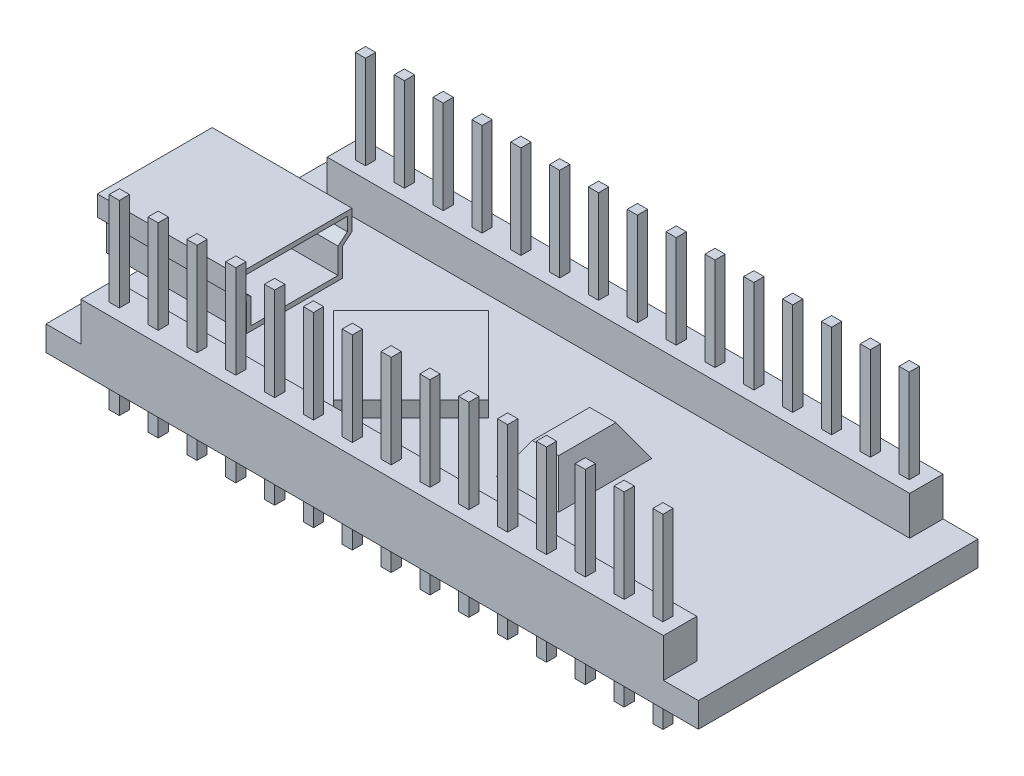
SolidWorks part; units mm, degrees
ref_plane "Front Plane" through (0, 0, 0) normal (0, 0, 1) x (1, 0, 0)
ref_plane "Top Plane" through (0, 0, 0) normal (0, 1, 0) x (1, 0, 0)
ref_plane "Right Plane" through (0, 0, 0) normal (1, 0, 0) x (0, 0, -1)
sketch "Sketch1" plane through (0, 0, 0) normal (0, 1, 0) x (1, 0, 0)
  line L1 (0, 0) -> (42, 0)
  line L2 (0, 0) -> (0, 18)
  line L3 (0, 18) -> (42, 18)
  line L4 (42, 0) -> (42, 18)
  dimension "D1" = 18
  dimension "D2" = 42
extrude "Boss-Extrude1" add sketch "Sketch1" along normal blind 1.6
sketch "Sketch2" plane through (0, 0, 0) normal (-1, 0, 0) x (0, 0, 1)
  line L0 (-9, 1.6) -> (-9, 5.2) construction
  line L1 (-18, 1.6) -> (0, 1.6) construction
  line L2 (-9, 1.6) -> (-12.1, 1.6)
  line L3 (-12.1, 1.6) -> (-12.1, 3.4)
  line L4 (-12.1, 3.4) -> (-12.7, 3.9)
  line L5 (-12.7, 3.9) -> (-12.7, 5.2)
  line L6 (-12.7, 5.2) -> (-9, 5.2)
  dimension "D1" = 3.6
  dimension "D2" = 3.7
  dimension "D3" = 3.1
  dimension "D4" = 1.8
  dimension "D5" = 1.3
extrude "Extrude-Thin1" add sketch "Sketch2" against normal blind 7 and the other way blind 2 thin
ref_plane "Plane1" through (0, 0, -9) normal (0, 0, 1) x (1, 0, 0)
mirror "Mirror1" about plane through (0, 0, -9) normal (0, 0, 1) of "Extrude-Thin1"
sketch "Sketch3" plane through (0, 1.6, 0) normal (0, -1, 0) x (1, 0, 0)
  line L0 (0, 0) -> (42, 0) construction
  line L1 (2.25, 0) -> (39.75, 0)
  line L2 (21, 0) -> (21, -2.1483)
  line L3 (2.25, -2.1483) -> (39.75, -2.1483)
  line L4 (39.75, 0) -> (39.75, -2.1483)
  line L5 (2.25, 0) -> (2.25, -2.1483)
  line M13 (0, 0) -> (42, 0)
  dimension "D1" = 18.75
  dimension "D2" = 2.1483
extrude "Boss-Extrude2" add sketch "Sketch3" against normal blind 2.5 contours L5 L2 L3 M13 | L1 L4 L3 L2
sketch "Sketch4" plane through (0, 4.1, 0) normal (0, -1, 0) x (1, 0, 0)
  line L0 (2.25, -1.0741) -> (3.6453, -1.0741) construction
  line L1 (2.25, 0) -> (2.25, -2.1483) construction
  line L3 (3.9727, -0.7468) -> (3.318, -0.7468)
  line L4 (3.9727, -0.7468) -> (3.9727, -1.4015)
  line L5 (3.9727, -1.4015) -> (3.318, -1.4015)
  line L6 (3.318, -0.7468) -> (3.318, -1.4015)
  line L7 (3.9727, -0.7468) -> (3.318, -1.4015) construction
  line L8 (3.9727, -1.4015) -> (3.318, -0.7468) construction
extrude "Boss-Extrude3" add sketch "Sketch4" along normal blind 6 and the other way blind 6
pattern_linear "LPattern1" count 15 spacing 2.5 along (1, 0, 0) of "Boss-Extrude3"
mirror "Mirror3" about plane through (0, 0, -9) normal (0, 0, 1) of "Boss-Extrude2"
mirror "Mirror4" about plane through (0, 0, -9) normal (0, 0, 1) of "LPattern1", "Boss-Extrude3"
sketch "Эскиз2" plane through (0, 1.6, 0) normal (0, 1, 0) x (1, 0, 0)
  line L0 (42, 9) -> (25, 9) construction
  line L1 (42, 0) -> (42, 18) construction
  line L3 (27, 12) -> (23, 12)
  line L4 (27, 12) -> (27, 6)
  line L5 (27, 6) -> (23, 6)
  line L6 (23, 12) -> (23, 6)
  line L7 (27, 12) -> (23, 6) construction
  line L8 (27, 6) -> (23, 12) construction
  dimension "D1" = 17
  dimension "D2" = 4
  dimension "D3" = 6
extrude "Бобышка-Вытянуть2" add sketch "Эскиз2" along normal blind 2 draft 30
sketch "Эскиз3" plane through (0, 1.6, 0) normal (0, 1, 0) x (1, 0, 0)
  line L0 (42, 9) -> (14.5, 9) construction
  line L1 (42, 0) -> (42, 18) construction
  line L2 (14.5, 9) -> (14.5, 4) construction
  line L3 (14.5, 4) -> (19.5, 9)
  line L4 (14.5, 4) -> (9.5, 9)
  line L5 (9.5, 9) -> (14.5, 14)
  line L6 (14.5, 14) -> (19.5, 9)
  dimension "D1" = 27.5
  dimension "D2" = 5
extrude "Бобышка-Вытянуть3" add sketch "Эскиз3" along normal blind 1
